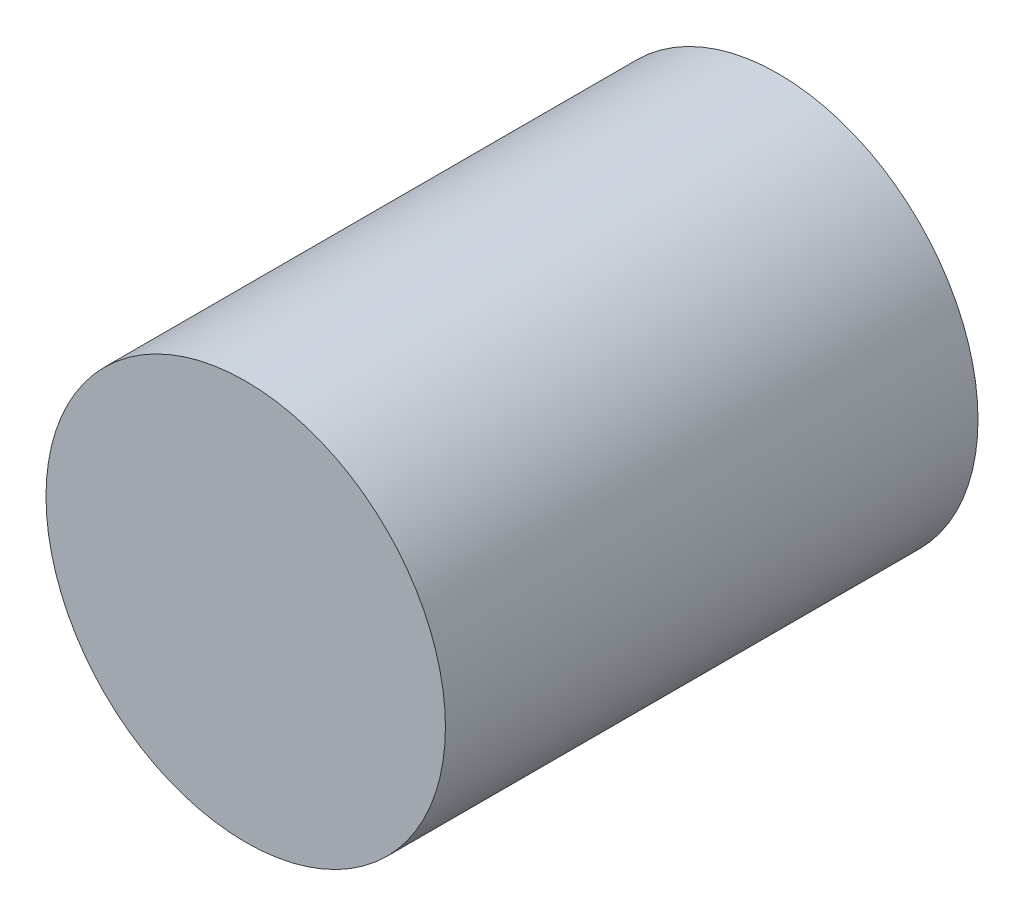
SolidWorks part; units mm, degrees
ref_plane "前视基准面" through (0, 0, 0) normal (0, 0, 1) x (1, 0, 0)
ref_plane "上视基准面" through (0, 0, 0) normal (0, 1, 0) x (1, 0, 0)
ref_plane "右视基准面" through (0, 0, 0) normal (1, 0, 0) x (0, 0, -1)
sketch "草图1" plane through (0, 0, 0) normal (0, 0, 1) x (1, 0, 0)
  circle A0 centre (0, 0) radius 15
extrude "凸台-拉伸1" add sketch "草图1" along normal blind 40 contours A0
